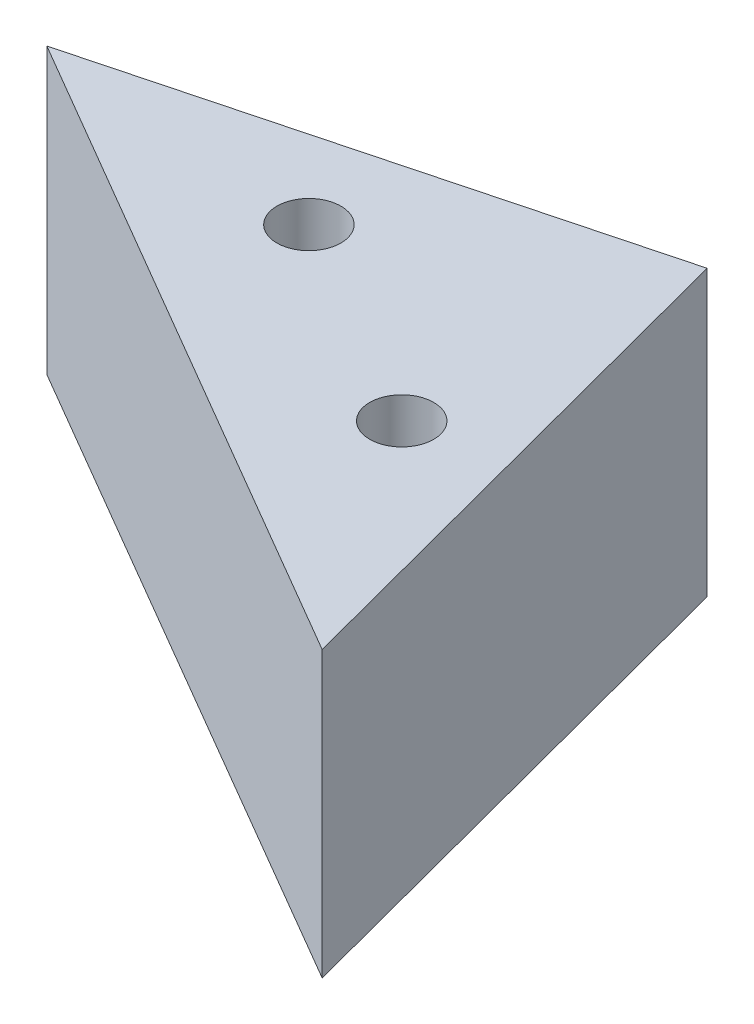
SolidWorks part; units mm, degrees
ref_plane "Front Plane" through (0, 0, 0) normal (0, 0, 1) x (1, 0, 0)
ref_plane "Top Plane" through (0, 0, 0) normal (0, 1, 0) x (1, 0, 0)
ref_plane "Right Plane" through (0, 0, 0) normal (1, 0, 0) x (0, 0, -1)
sketch "Sketch1" plane through (0, 0, 0) normal (0, 1, 0) x (1, 0, 0)
  line L0 (0, 0) -> (46.4263, -27.0663)
  line L1 (0, 0) -> (36.7464, 9.6801)
  line L2 (36.7464, 9.6801) -> (46.4263, -27.0663)
  dimension "D1" = 53.74
  dimension "D2" = 38
  dimension "D3" = 38
extrude "Boss-Extrude1" add sketch "Sketch1" against normal blind 20
sketch "Sketch8" plane through (0, 0, 0) normal (0, 1, 0) x (1, 0, 0)
  line L0 (46.4263, -27.0663) -> (41.5863, -8.6931)
  line L1 (46.4263, -27.0663) -> (36.7464, 9.6801) construction
  line L2 (41.5863, -8.6931) -> (35.3008, -10.3489)
  line L3 (0, 0) -> (18.3732, 4.84)
  line L4 (36.7464, 9.6801) -> (0, 0) construction
  line L5 (18.3732, 4.84) -> (20.0855, -1.66)
  circle A0 centre (20.0855, -1.66) radius 2.25
  circle A1 centre (35.3008, -10.3489) radius 2.25
  dimension "D3" = 4.5
  dimension "D4" = 4.5
  dimension "D1" = 6.5
  dimension "D2" = 6.5
extrude "Cut-Extrude3" cut sketch "Sketch8" against normal blind 5
